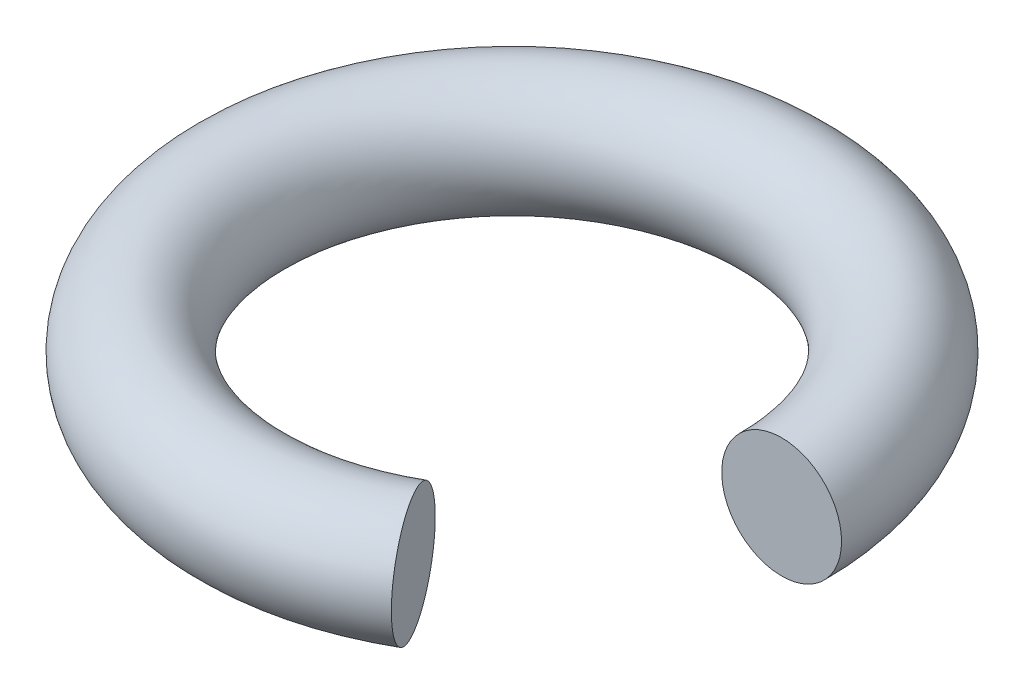
SolidWorks part; units mm, degrees
ref_plane "Front Plane" through (0, 0, 0) normal (0, 0, 1) x (1, 0, 0)
ref_plane "Top Plane" through (0, 0, 0) normal (0, 1, 0) x (1, 0, 0)
ref_plane "Right Plane" through (0, 0, 0) normal (1, 0, 0) x (0, 0, -1)
sketch "Reconstructed nominal axial profile" plane through (0, 0, 0) normal (0, 0, 1) x (1, 0, 0)
  line L0 (0, -500) -> (0, 50) construction
  circle A0 centre (2.7, 0) radius 0.6
revolve "Native revolved geometry" add sketch "Reconstructed nominal axial profile" angle 300 about L0
